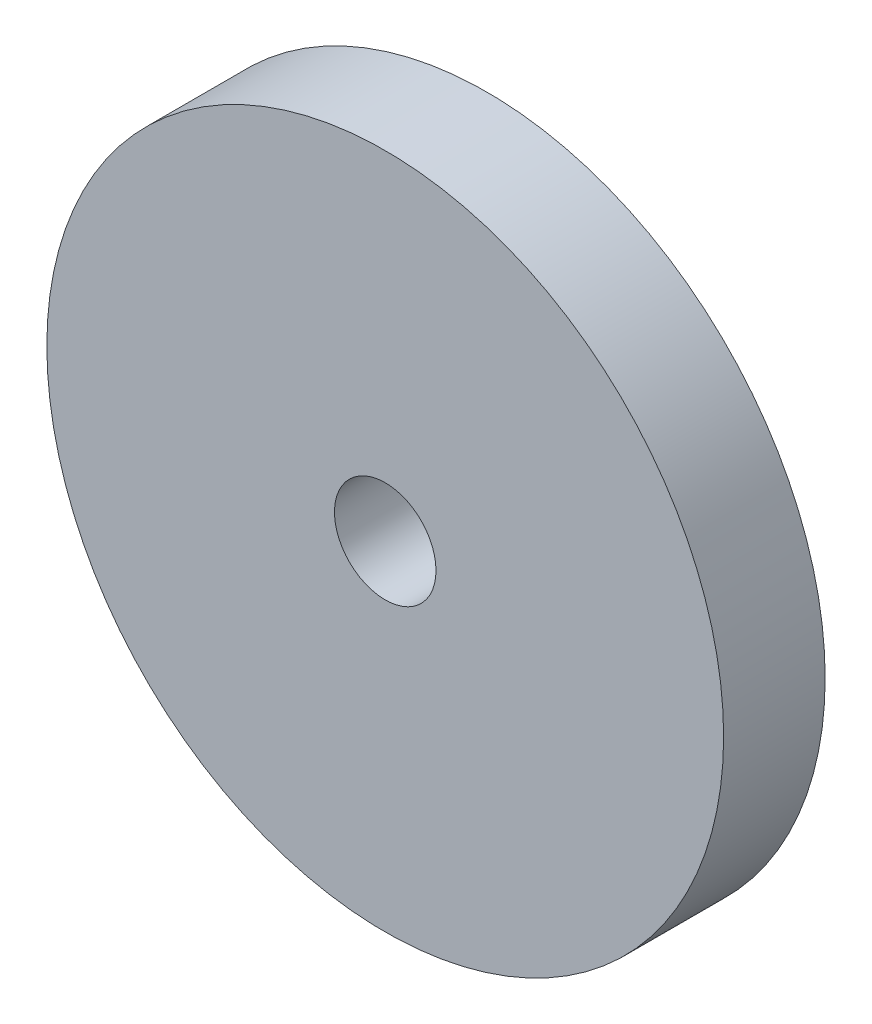
SolidWorks part; units mm, degrees
ref_plane "Front Plane" through (0, 0, 0) normal (0, 0, 1) x (1, 0, 0)
ref_plane "Top Plane" through (0, 0, 0) normal (0, 1, 0) x (1, 0, 0)
ref_plane "Right Plane" through (0, 0, 0) normal (1, 0, 0) x (0, 0, -1)
sketch "Sketch1" plane through (0, 0, 0) normal (0, 0, 1) x (1, 0, 0)
  circle A0 centre (-70.7408, 50.2184) radius 10
  circle A1 centre (-70.7408, 50.2184) radius 1.5
extrude "Boss-Extrude1" add sketch "Sketch1" along normal blind 3
